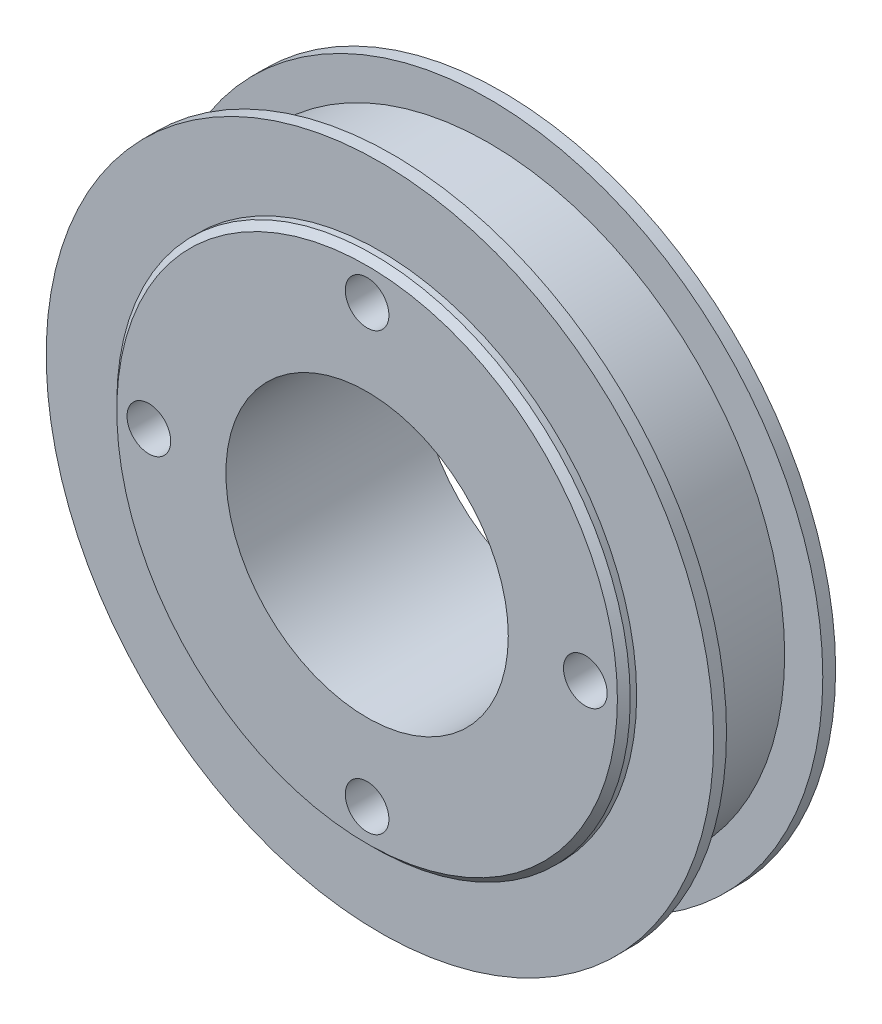
SolidWorks part; units mm, degrees
ref_plane "Front Plane" through (0, 0, 0) normal (0, 0, 1) x (1, 0, 0)
ref_plane "Top Plane" through (0, 0, 0) normal (0, 1, 0) x (1, 0, 0)
ref_plane "Right Plane" through (0, 0, 0) normal (1, 0, 0) x (0, 0, -1)
sketch "Sketch1" plane through (0, 0, 0) normal (0, 0, 1) x (1, 0, 0)
  circle A0 centre (0, 0) radius 13
extrude "Boss-Extrude1" add sketch "Sketch1" along normal blind 3.5
sketch "Sketch2" plane through (0, 0, 3.5) normal (0, 0, 1) x (1, 0, 0)
  circle A0 centre (0, 0) radius 20
extrude "Boss-Extrude2" add sketch "Sketch2" along normal blind 1
sketch "Sketch3" plane through (0, 0, 4.5) normal (0, 0, 1) x (1, 0, 0)
  circle A0 centre (0, 0) radius 26
extrude "Boss-Extrude3" add sketch "Sketch3" along normal blind 1
sketch "Sketch4" plane through (0, 0, 5.5) normal (0, 0, 1) x (1, 0, 0)
  circle A0 centre (0, 0) radius 23.03
extrude "Boss-Extrude4" add sketch "Sketch4" along normal blind 7.5
sketch "Sketch5" plane through (0, 0, 13) normal (0, 0, 1) x (1, 0, 0)
  circle A0 centre (0, 0) radius 26
extrude "Boss-Extrude5" add sketch "Sketch5" along normal blind 1
sketch "Sketch6" plane through (0, 0, 14) normal (0, 0, 1) x (1, 0, 0)
  circle A0 centre (0, 0) radius 20
extrude "Boss-Extrude6" add sketch "Sketch6" along normal blind 1
sketch "Sketch7" plane through (0, 0, 15) normal (0, 0, 1) x (1, 0, 0)
  circle A0 centre (0, 0) radius 11
extrude "Cut-Extrude1" cut sketch "Sketch7" against normal through all
sketch "Sketch10" plane through (0, 0, 3.5) normal (0, 0, -1) x (-1, 0, 0)
  point P0 (0, 17)
  point P2 (17, 0)
  point P4 (0, -17)
  point P6 (-17, 0)
hole_wizard "Tap Drill for M3x0.5 Tap1" positions "Sketch10" profile "Sketch11" hole size "M3x0.5" standard "JIS" end condition through all
sketch "Sketch11" plane through (0, 17, 3.5) normal (1, 0, 0) x (0, 1, 0)
  line L0 (0, 0) -> (0, 11.5)
  line L1 (0, 11.5) -> (1.7, 11.5)
  line L2 (1.7, 11.5) -> (1.7, 0)
  line L5 (1.7, 0) -> (0, 0)
  line L11 (0, -6.35) -> (0, 107.95) construction
  dimension "Thru Hole Dia." = 3.4
  dimension "Thru Hole Depth" = 11.5
chamfer "Chamfer1" distance 0.5 angle 45 1 edges at (20, 0, 15)
